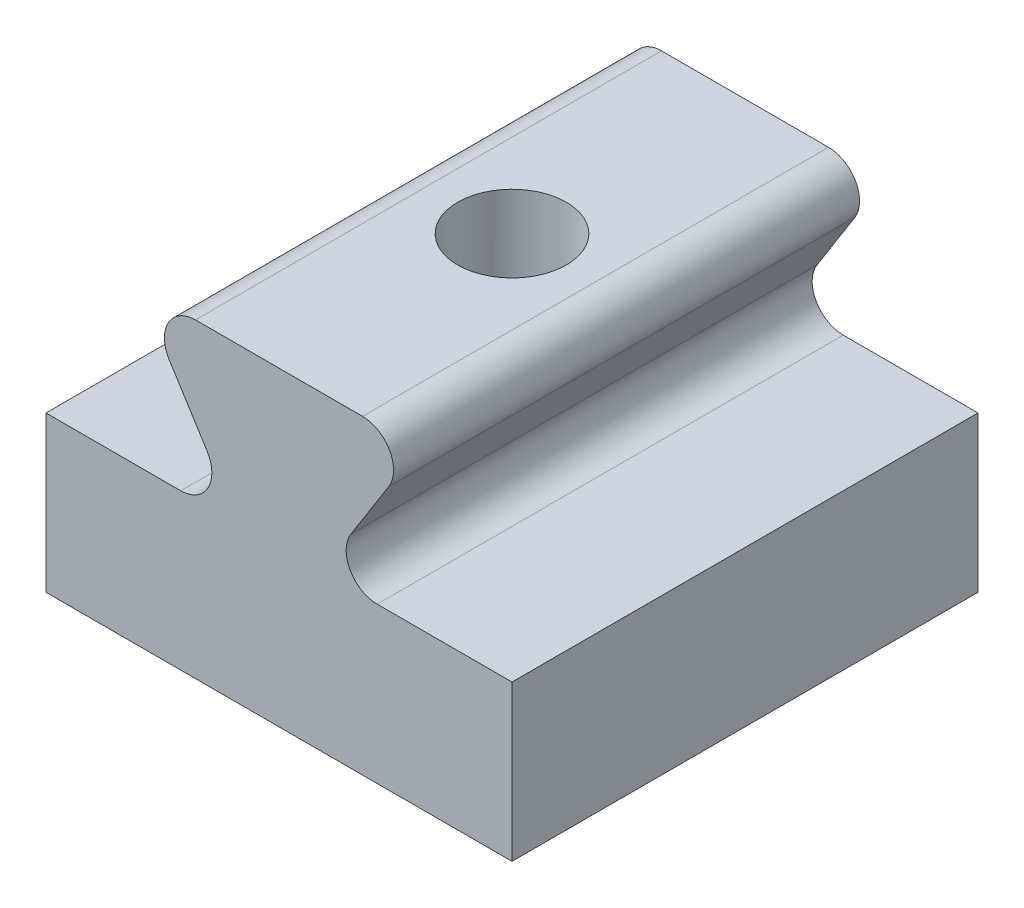
SolidWorks part; units mm, degrees
ref_plane "Plano frontal" through (0, 0, 0) normal (0, 0, 1) x (1, 0, 0)
ref_plane "Plano superior" through (0, 0, 0) normal (0, 1, 0) x (1, 0, 0)
ref_plane "Plano direito" through (0, 0, 0) normal (1, 0, 0) x (0, 0, -1)
sketch "Esboço1" plane through (0, 0, 0) normal (0, 0, 1) x (1, 0, 0)
  line L0 (-1.35, 0) -> (-4.5, 5)
  line L1 (-7.5, 0) -> (7.5, 0)
  line L2 (-7.5, 0) -> (-7.5, -5)
  line L3 (-7.5, -5) -> (7.5, -5)
  line L4 (7.5, 0) -> (7.5, -5)
  line L5 (4.5, 5) -> (1.35, 0)
  line L6 (-4.5, 5) -> (4.5, 5)
  point P4 (0, 0)
  point P10 (4.7838, 3.9392)
  point P11 (-4.5, 4.0892)
  point P12 (0, 5)
  dimension "D1" = 9
  dimension "D2" = 5
  dimension "D3" = 2.7
  dimension "D4" = 5
  dimension "D5" = 15
extrude "Ressalto-extrusão1" add sketch "Esboço1" along normal blind 15 contours L4 L1 L2 L3 | L6 L0 L1 L5
fillet "Filete1" radius 1 4 edges at (-1.35, 0, 7.5) (-4.5, 5, 7.5) (4.5, 5, 7.5) (1.35, 0, 7.5)
sketch "Esboço2" plane through (0, 5, 0) normal (0, 1, 0) x (1, 0, 0)
  line L0 (7.5, -15) -> (7.5, 0) construction
  circle A0 centre (0, -7.5) radius 1.75
  dimension "D2" = 3.5
  dimension "D1" = 7.5
  dimension "D3" = 7.5
extrude "Corte-extrusão1" cut sketch "Esboço2" against normal blind 15
